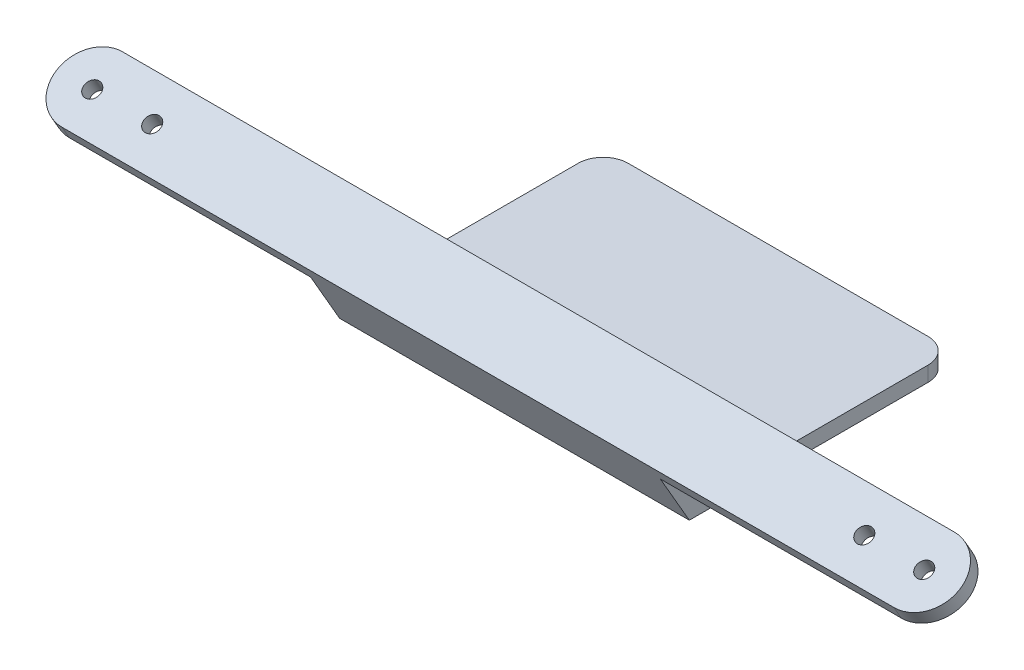
SolidWorks part; units mm, degrees
ref_plane "前视基准面" through (0, 0, 0) normal (0, 0, 1) x (1, 0, 0)
ref_plane "上视基准面" through (0, 0, 0) normal (0, 1, 0) x (1, 0, 0)
ref_plane "右视基准面" through (0, 0, 0) normal (1, 0, 0) x (0, 0, -1)
sketch "草图1" plane through (0, 0, 0) normal (0, 1, 0) x (1, 0, 0)
  line L1 (0, 0) -> (70, 0)
  line L2 (0, 0) -> (0, 50)
  line L3 (0, 50) -> (70, 50)
  line L4 (70, 0) -> (70, 50)
  dimension "D1" = 70
  dimension "D2" = 50
extrude "凸台-拉伸1" add sketch "草图1" along normal blind 3
sketch "草图2" plane through (0, 0, 0) normal (-1, 0, 0) x (0, 0, 1)
  line L0 (0, 15) -> (-6.0622, 18.5)
  line L1 (0, 0) -> (4, 0)
  line L2 (0, 0) -> (0, 15)
  line L4 (4, 0) -> (4, 15)
  line L5 (-6.0622, 18.5) -> (-4.5622, 21.0981)
  line L6 (-4.5622, 21.0981) -> (4, 16.1547)
  line L7 (4, 16.1547) -> (4, 15)
  dimension "D1" = 15
  dimension "D2" = 4
  dimension "D3" = 7
  dimension "D4" = 120
  dimension "D5" = 3
extrude "凸台-拉伸2" add sketch "草图2" against normal up to surface (70 mm away) up to face at (70, 1.5, -25)
sketch "草图3" plane through (0, 13.8481, 7.9952) normal (0, 0.866, 0.5) x (1, 0, 0)
  line L0 (-36.265, 4.6132) -> (106.265, 4.6132) construction
  line L1 (35, 44.8013) -> (35, 4.6132) construction
  line L2 (70, 44.8013) -> (0, 44.8013) construction
  line L3 (-48.265, 4.6132) -> (-36.265, 4.6132) construction
  line L4 (-48.265, 11.6132) -> (-36.265, 11.6132)
  line L5 (-48.265, -2.3868) -> (-36.265, -2.3868)
  line L6 (106.265, 4.6132) -> (118.265, 4.6132) construction
  line L7 (106.265, 11.6132) -> (118.265, 11.6132)
  line L8 (106.265, -2.3868) -> (118.265, -2.3868)
  line L9 (-36.265, 11.6132) -> (106.265, 11.6132)
  line L10 (-36.265, -2.3868) -> (106.265, -2.3868)
  circle A0 centre (-36.265, 4.6132) radius 1.6
  circle A1 centre (106.265, 4.6132) radius 1.6
  circle A2 centre (-48.265, 4.6132) radius 1.6
  circle A3 centre (118.265, 4.6132) radius 1.6
  arc A4 (-48.265, 11.6132) -> (-48.265, -2.3868) centre (-48.265, 4.6132) ccw
  arc A7 (118.265, -2.3868) -> (118.265, 11.6132) centre (118.265, 4.6132) ccw
  point P13 (-42.265, 4.6132)
  point P18 (112.265, 4.6132)
  dimension "D2" = 3.2
  dimension "D3" = 3.2
  dimension "D6" = 7
  dimension "D1" = 142.53
  dimension "D4" = 12
  dimension "D5" = 12
  dimension "D7" = 14
extrude "凸台-拉伸3" add sketch "草图3" against normal up to surface (3 mm away) up to face at (35, 16.75, -3.0311)
sketch "草图4" plane through (0, 11.25, 6.4952) normal (0, -0.866, -0.5) x (1, 0, 0)
  line L0 (-48.265, 2.3868) -> (118.265, 2.3868) construction
  line L1 (70, -2.8812) -> (0, -2.8812)
  line L2 (70, -2.8812) -> (70, 2.3868)
  line L3 (70, 2.3868) -> (0, 2.3868)
  line L4 (0, -2.8812) -> (0, 2.3868)
extrude "凸台-拉伸4" add sketch "草图4" along normal up to surface up to face at (35, 6.3453, 4)
fillet "圆角1" radius 5 1 edges at (35, 3, 0)
sketch "草图5" plane through (0, -1.1934, 2.067) normal (0, -0.5, 0.866) x (1, 0, 0)
  line L1 (0, 3.866) -> (70, 3.866)
  line L2 (0, 3.866) -> (0, -25)
  line L3 (0, -25) -> (70, -25)
  line L4 (70, 3.866) -> (70, -25)
extrude "切除-拉伸1" cut sketch "草图5" along normal through all
sketch "草图6" plane through (0, 5.8066, -10.0574) normal (0, 0.5, -0.866) x (-1, 0, 0)
  line L1 (-70, 15.9904) -> (0, 15.9904)
  line L2 (-70, 15.9904) -> (-70, 12.9904)
  line L3 (-70, 12.9904) -> (0, 12.9904)
  line L4 (0, 15.9904) -> (0, 12.9904)
extrude "切除-拉伸2" cut sketch "草图6" along normal through all
fillet "圆角2" radius 5 2 edges at (0, 1.5, -50) (70, 1.5, -50)
sketch "草图7" plane through (0, 3, 0) normal (0, 1, 0) x (1, 0, 0)
  line L0 (35, 50) -> (35, 3.5622) construction
  line L1 (65, 50) -> (5, 50) construction
  line L2 (118.265, 3.5622) -> (-48.265, 3.5622) construction
  circle A0 centre (10, 40) radius 1.6
  circle A1 centre (60, 40) radius 1.6
  circle A2 centre (35, 10) radius 1.6
  dimension "D1" = 3.2
  dimension "D2" = 40
  dimension "D3" = 50
  dimension "D4" = 10
ref_plane "基准面1" through (0, 13.8481, 7.9952) normal (0, 0.866, 0.5) x (1, 0, 0)
